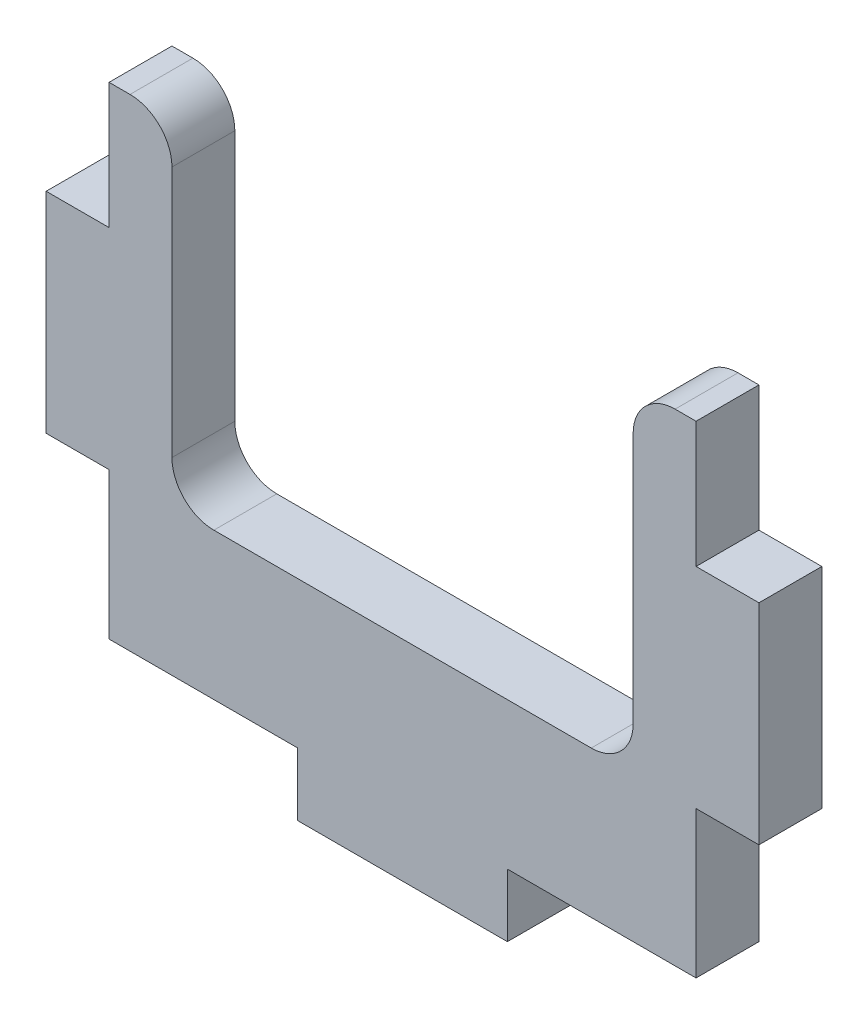
SolidWorks part; units mm, degrees
ref_plane "前视基准面" through (0, 0, 0) normal (0, 0, 1) x (1, 0, 0)
ref_plane "上视基准面" through (0, 0, 0) normal (0, 1, 0) x (1, 0, 0)
ref_plane "右视基准面" through (0, 0, 0) normal (1, 0, 0) x (0, 0, -1)
other "Configuration Table"
sketch "草图1" plane through (0, 0, 0) normal (0, 0, 1) x (1, 0, 0)
  line L0 (0, 11.0299) -> (0, -10.8894) construction
  line L1 (-14, 12) -> (14, 12)
  line L2 (-14, 12) -> (-14, -12)
  line L3 (-14, -12) -> (14, -12)
  line L4 (14, 12) -> (14, -12)
  line L5 (-14, 12) -> (14, -12) construction
  line L6 (-14, -12) -> (14, 12) construction
  line L7 (-14, -5) -> (-17, -5)
  line L8 (-14, -5) -> (-14, 5)
  line L9 (-14, 5) -> (-17, 5)
  line L10 (-17, -5) -> (-17, 5)
  line L11 (14, 5) -> (17, 5)
  line L12 (17, -5) -> (17, 5)
  line L13 (14, -5) -> (17, -5)
  line L14 (14, -5) -> (14, 5)
  line L16 (-5, -12) -> (5, -12)
  line L17 (-5, -12) -> (-5, -15)
  line L18 (-5, -15) -> (5, -15)
  line L19 (5, -12) -> (5, -15)
  point P0 (0, 0)
  point P10 (-17, 0)
  point P21 (0, -15)
  dimension "D1" = 28
  dimension "D2" = 24
  dimension "D3" = 3
  dimension "D4" = 10
extrude "凸台-拉伸1" add sketch "草图1" along normal blind 3 contours L4 L1 L2 L3 | L10 L7 L2 L9 | L4 L13 L12 L11 | L19 L3 L17 L18
sketch "草图2" plane through (0, 0, 3) normal (0, 0, 1) x (1, 0, 0)
  line L0 (-17, -5) -> (-17, 5) construction
  line L1 (-29, 1.5) -> (-5, 1.5)
  line L2 (-29, 1.5) -> (-29, -1.5)
  line L3 (-29, -1.5) -> (-5, -1.5)
  line L4 (-5, 1.5) -> (-5, -1.5)
  line L5 (-29, 1.5) -> (-5, -1.5) construction
  line L6 (-29, -1.5) -> (-5, 1.5) construction
  line L7 (-17, 0) -> (-9.5, 0) construction
  line L8 (0, 6.8052) -> (0, -6.843) construction
  line L9 (-11, 3) -> (-8, 3)
  line L10 (-11, 3) -> (-11, -3)
  line L11 (-11, -3) -> (-8, -3)
  line L12 (-8, 3) -> (-8, -3)
  line L13 (-11, 3) -> (-8, -3) construction
  line L14 (-11, -3) -> (-8, 3) construction
  line L15 (11, -3) -> (8, 3) construction
  line L16 (11, 3) -> (8, -3) construction
  line L17 (17, 0) -> (9.5, 0) construction
  line L18 (29, -1.5) -> (5, 1.5) construction
  line L19 (29, 1.5) -> (5, -1.5) construction
  line L20 (8, 3) -> (8, -3)
  line L21 (11, -3) -> (8, -3)
  line L22 (11, 3) -> (11, -3)
  line L23 (11, 3) -> (8, 3)
  line L24 (5, 1.5) -> (5, -1.5)
  line L25 (29, -1.5) -> (5, -1.5)
  line L26 (29, 1.5) -> (29, -1.5)
  line L27 (29, 1.5) -> (5, 1.5)
  line L28 (-14, -12) -> (14, 12) construction
  line L29 (-5, -15) -> (5, -15) construction
  line L30 (-1.5, -3) -> (1.5, -3)
  line L31 (-1.5, -3) -> (-1.5, -27)
  line L32 (-1.5, -27) -> (1.5, -27)
  line L33 (1.5, -3) -> (1.5, -27)
  line L34 (-1.5, -3) -> (1.5, -27) construction
  line L35 (-1.5, -27) -> (1.5, -3) construction
  line L36 (0, -15) -> (0, -7.5) construction
  line L38 (-3, -6) -> (3, -6)
  line L39 (-3, -6) -> (-3, -9)
  line L40 (-3, -9) -> (3, -9)
  line L41 (3, -6) -> (3, -9)
  line L42 (-3, -6) -> (3, -9) construction
  line L43 (-3, -9) -> (3, -6) construction
  point P0 (-17, 0)
  point P26 (17, 0)
  point P31 (0, -15)
  line M7 (-17, 5) -> (-17, -5)
  line M13 (17, -5) -> (17, 5)
  line M42 (-5, -15) -> (5, -15)
  dimension "D1" = 3
  dimension "D2" = 24
  dimension "D3" = 3
  dimension "D4" = 6
  dimension "D5" = 6
  dimension "D6" = 24
  dimension "D7" = 3
  dimension "D8" = 3
  dimension "D9" = 6
  dimension "D10" = 6
extrude "切除-拉伸1" [suppressed] cut sketch "草图2" against normal blind 3 contours L10 L1 L3 M7 | L12 L9 L10 L1 | L12 L1 L10 L3 | L12 L3 L10 L11 | L1 L12 L3 L4 | L20 L27 L24 L25 | L27 L22 L23 L20 | L22 L27 L20 L25 | L22 L25 L20 L21 | L27 L22 L25 M13 | L39 L40 L31 L38 | L31 L38 L33 L30 | L31 L40 L33 L38 | L41 L38 L33 L40 | L40 L31 L33 M42
sketch "草图3" plane through (0, 0, 3) normal (0, 0, 1) x (1, 0, 0)
  line L0 (14, 12) -> (14, 5) construction
  line L1 (-14, 12) -> (14, 12)
  line L2 (-14, 12) -> (-14, 11)
  line L3 (-14, 11) -> (14, 11)
  line L4 (14, 12) -> (14, 11)
  dimension "D1" = 1
extrude "切除-拉伸2" cut sketch "草图3" against normal blind 3
sketch "草图4" plane through (0, 0, 3) normal (0, 0, 1) x (1, 0, 0)
  line L0 (-14, 11) -> (14, 11) construction
  line L1 (-11, 11) -> (11, 11)
  line L2 (-11, 11) -> (-11, -5)
  line L3 (-11, -5) -> (11, -5)
  line L4 (11, 11) -> (11, -5)
  point P6 (0, -5)
  dimension "D1" = 22
  dimension "D2" = 16
extrude "切除-拉伸3" cut sketch "草图4" against normal through all both and the other way through all
fillet "圆角1" radius 2 4 edges at (-11, -5, 1.5) (11, -5, 1.5) (11, 11, 1.5) (-11, 11, 1.5)
